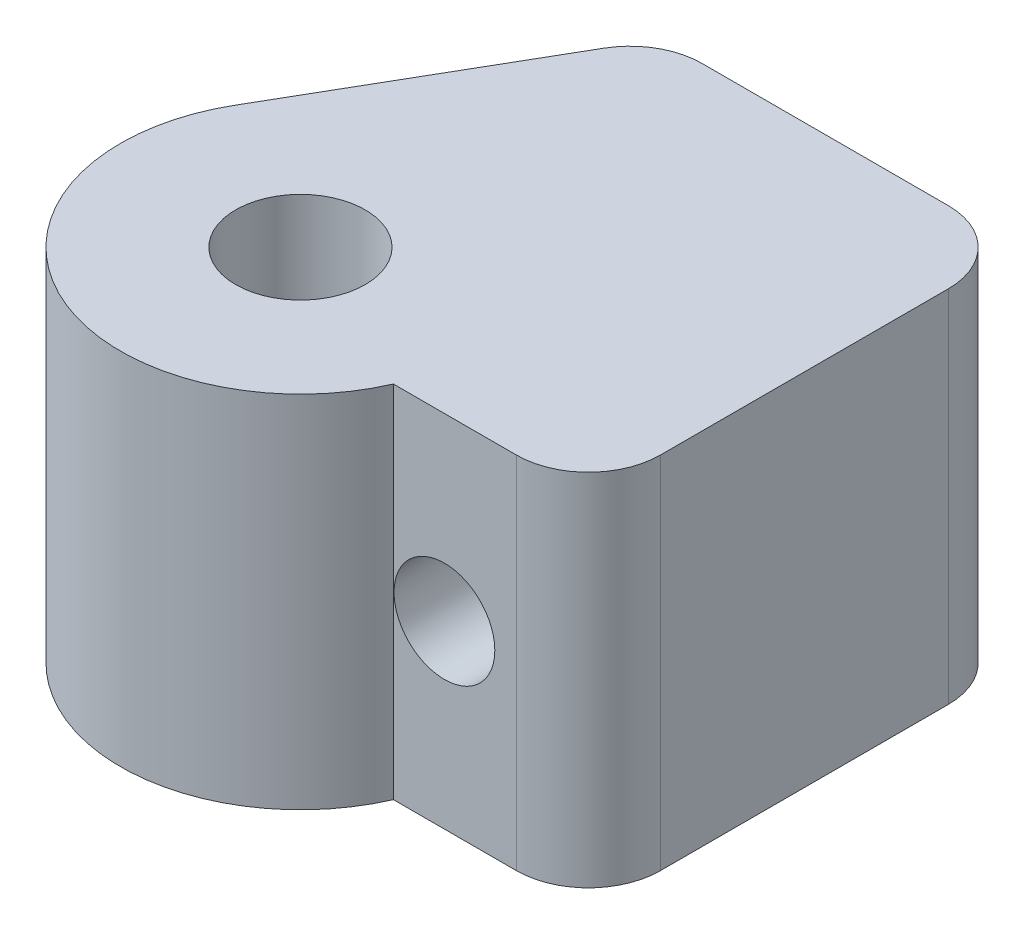
SolidWorks part; units mm, degrees
ref_plane "Front Plane" through (0, 0, 0) normal (0, 0, 1) x (1, 0, 0)
ref_plane "Top Plane" through (0, 0, 0) normal (0, 1, 0) x (1, 0, 0)
ref_plane "Right Plane" through (0, 0, 0) normal (1, 0, 0) x (0, 0, -1)
sketch "Sketch1" plane through (0, 0, 0) normal (0, 1, 0) x (1, 0, 0)
  line L0 (-5.4993, 3.175) -> (0, 12.7)
  line L3 (0, 12.7) -> (12.7, 12.7)
  line L4 (12.7, -2.54) -> (12.7, 12.7)
  line L5 (5.8199, -2.54) -> (12.7, -2.54)
  circle A0 centre (0, 0) radius 2.286
  arc A1 (-5.4993, 3.175) -> (5.8199, -2.54) centre (0, 0) ccw
  dimension "D2" = 4.572
  dimension "D3" = 6.35
  dimension "D1" = 12.7
  dimension "D4" = 15.24
  dimension "D5" = 2.54
extrude "Boss-Extrude1" add sketch "Sketch1" along normal blind 12.7 contours L4 L3 L0 A1 L5 | A0
sketch "Sketch2" plane through (0, 0, 2.54) normal (0, 0, 1) x (1, 0, 0)
  line L1 (12.7, 12.7) -> (12.7, 0) construction
  circle A0 centre (7.62, 6.35) radius 1.778
  point P5 (12.7, 6.35)
  dimension "D2" = 3.556
  dimension "D1" = 5.08
extrude "Cut-Extrude1" cut sketch "Sketch2" against normal through all
fillet "Fillet1" radius 2.54 3 edges at (0, 6.35, -12.7) (12.7, 6.35, -12.7) (12.7, 6.35, 2.54)
